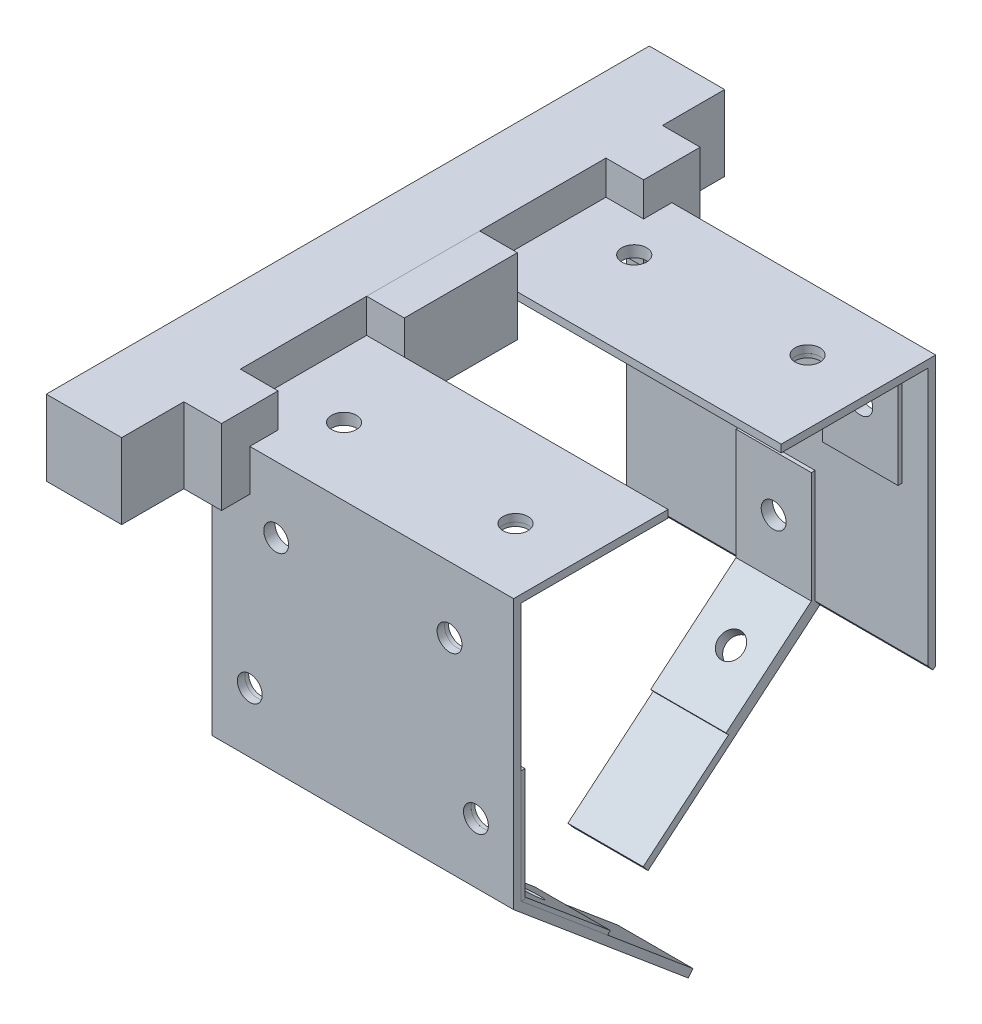
SolidWorks part; units mm, degrees
ref_plane "Front Plane" through (0, 0, 0) normal (0, 0, 1) x (1, 0, 0)
ref_plane "Top Plane" through (0, 0, 0) normal (0, 1, 0) x (1, 0, 0)
ref_plane "Right Plane" through (0, 0, 0) normal (1, 0, 0) x (0, 0, -1)
sketch "Sketch2" plane through (0, 0, 0) normal (1, 0, 0) x (0, 0, -1)
  line L0 (-19.05, 0) -> (19.05, 0) construction
  line L1 (-19.05, 0) -> (-69.85, 0)
  line L2 (-69.85, 0) -> (-69.85, -88.9)
  line L3 (-69.85, -88.9) -> (-11.4774, -137.8804)
  line L4 (19.05, 0) -> (69.85, 0)
  line L5 (69.85, 0) -> (69.85, -88.9)
  line L6 (69.85, -88.9) -> (11.4774, -137.8804)
  point P8 (0, 0)
  dimension "D1" = 38.1
  dimension "D2" = 50.8
  dimension "D3" = 88.9
  dimension "D4" = 76.2
  dimension "D5" = 130
  dimension "D6" = 130
extrude "Extrude-Thin1" add sketch "Sketch2" along normal blind 101.6 thin thin type mid plane wall 2.54
sketch "Sketch6" plane through (0, -85.5902, -71.8187) normal (0, 0.766, 0.6428) x (1, 0, 0)
  line L0 (101.6, -4.2278) -> (0, -4.2278) construction
  line L1 (38.1, -4.2278) -> (63.5, -4.2278)
  line L2 (38.1, -4.2278) -> (38.1, -79.8356)
  line L3 (38.1, -79.8356) -> (63.5, -79.8356)
  line L4 (63.5, -4.2278) -> (63.5, -79.8356)
  line L5 (101.6, -79.8356) -> (0, -79.8356) construction
  line L8 (63.5, -4.2278) -> (101.6, -4.2278) construction
  line L9 (38.1, -4.2278) -> (0, -4.2278) construction
  line L11 (38.1, -4.2278) -> (0, -4.2278)
  line L12 (38.1, -4.2278) -> (38.1, -79.8356)
  line L13 (38.1, -79.8356) -> (0, -79.8356)
  line L14 (0, -4.2278) -> (0, -79.8356)
  line L15 (101.6, -79.8356) -> (63.5, -79.8356)
  line L16 (101.6, -79.8356) -> (101.6, -4.2278)
  line L17 (101.6, -4.2278) -> (63.5, -4.2278)
  line L18 (63.5, -79.8356) -> (63.5, -4.2278)
  line M5 (0, -4.2278) -> (0, -79.8356)
  line M6 (0, -79.8356) -> (101.6, -79.8356)
  line M7 (101.6, -79.8356) -> (101.6, -4.2278)
  line M8 (101.6, -4.2278) -> (0, -4.2278)
  dimension "D1" = 25.4
extrude "Cut-Extrude2" cut sketch "Sketch6" against normal blind 11.684 contours L4 M8 M6 M7 | L2 M8 M5 M6
sketch "Sketch7" plane through (0, -85.5902, 71.8187) normal (0, 0.766, -0.6428) x (1, 0, 0)
  line L0 (101.6, 79.8356) -> (0, 79.8356) construction
  line L1 (101.6, 4.2278) -> (76.2, 4.2278)
  line L2 (101.6, 4.2278) -> (101.6, 79.8356)
  line L3 (101.6, 79.8356) -> (76.2, 79.8356)
  line L4 (76.2, 4.2278) -> (76.2, 79.8356)
  line L6 (0, 4.2278) -> (25.4, 4.2278)
  line L7 (0, 4.2278) -> (0, 79.8356)
  line L8 (0, 79.8356) -> (25.4, 79.8356)
  line L9 (25.4, 4.2278) -> (25.4, 79.8356)
  line L10 (76.2, 4.2278) -> (25.4, 4.2278)
  line L11 (76.2, 4.2278) -> (76.2, 79.8356)
  line L12 (76.2, 79.8356) -> (25.4, 79.8356)
  line L13 (25.4, 4.2278) -> (25.4, 79.8356)
  line M4 (0, 4.2278) -> (101.6, 4.2278)
  line M6 (101.6, 79.8356) -> (0, 79.8356)
  dimension "D1" = 25.4
  dimension "D2" = 25.4
extrude "Cut-Extrude3" cut sketch "Sketch7" against normal blind 11.684 contours L9 L4 M4 M6
sketch "Sketch8" plane through (0, 0, 68.58) normal (0, 0, -1) x (-1, 0, 0)
  line L0 (-76.2, -88.3078) -> (-76.2, -50.2078)
  line L1 (-76.2, -50.2078) -> (-101.6, -50.2078)
  line L2 (-101.6, -1.27) -> (-101.6, -88.3078) construction
  line L3 (-101.6, -50.2078) -> (-101.6, -88.3078)
  line L4 (-101.6, -88.3078) -> (-76.2, -88.3078)
  line L5 (0, -88.3078) -> (0, -50.2078)
  line L6 (0, -1.27) -> (0, -88.3078) construction
  line L7 (0, -50.2078) -> (-25.4, -50.2078)
  line L8 (-25.4, -50.2078) -> (-25.4, -88.3078)
  line L9 (-25.4, -88.3078) -> (0, -88.3078)
  line L10 (-101.6, -1.27) -> (0, -1.27) construction
  line L11 (-92.71, -1.27) -> (-67.31, -1.27)
  line L12 (-92.71, -1.27) -> (-92.71, -39.37)
  line L13 (-92.71, -39.37) -> (-67.31, -39.37)
  line L14 (-67.31, -1.27) -> (-67.31, -39.37)
  line L16 (-8.89, -1.27) -> (-34.29, -1.27)
  line L17 (-8.89, -1.27) -> (-8.89, -39.37)
  line L18 (-8.89, -39.37) -> (-34.29, -39.37)
  line L19 (-34.29, -1.27) -> (-34.29, -39.37)
  dimension "D1" = 38.1
  dimension "D2" = 8.89
  dimension "D3" = 8.89
extrude "Boss-Extrude1" add sketch "Sketch8" along normal blind 1.27 separate body
sketch "Sketch10" plane through (0, -85.5902, 71.8187) normal (0, 0.766, -0.6428) x (1, 0, 0)
  line L0 (76.2, 4.2278) -> (76.2, 79.8356) construction
  line L1 (101.6, 4.2278) -> (76.2, 4.2278)
  line L2 (101.6, 4.2278) -> (101.6, 42.3278)
  line L3 (101.6, 42.3278) -> (76.2, 42.3278)
  line L4 (76.2, 4.2278) -> (76.2, 42.3278)
  line L10 (0, 4.2278) -> (0, 79.8356) construction
  line L11 (25.4, 4.2278) -> (0, 4.2278)
  line L12 (25.4, 4.2278) -> (25.4, 42.3278)
  line L13 (25.4, 42.3278) -> (0, 42.3278)
  line L14 (0, 4.2278) -> (0, 42.3278)
  dimension "D1" = 38.1
  dimension "D2" = 38.1
extrude "Boss-Extrude2" add sketch "Sketch10" along normal blind 1.27 separate body
sketch "Sketch12" plane through (0, -85.5902, -71.8187) normal (0, 0.766, 0.6428) x (1, 0, 0)
  line L0 (63.5, -4.2278) -> (63.5, -79.8356) construction
  line L1 (38.1, -4.2278) -> (63.5, -4.2278)
  line L2 (38.1, -4.2278) -> (38.1, -42.3278)
  line L3 (38.1, -42.3278) -> (63.5, -42.3278)
  line L4 (63.5, -4.2278) -> (63.5, -42.3278)
  dimension "D1" = 38.1
extrude "Boss-Extrude3" add sketch "Sketch12" along normal blind 1.27 separate body
sketch "Sketch13" plane through (0, 0, -68.58) normal (0, 0, 1) x (1, 0, 0)
  line L0 (38.1, -88.3078) -> (0, -88.3078) construction
  line L1 (38.1, -88.3078) -> (63.5, -88.3078)
  line L2 (38.1, -88.3078) -> (38.1, -50.2078)
  line L3 (38.1, -50.2078) -> (63.5, -50.2078)
  line L4 (63.5, -88.3078) -> (63.5, -50.2078)
  line L5 (38.1, -88.3078) -> (0, -88.3078) construction
  line L6 (63.5, -88.3078) -> (101.6, -88.3078) construction
  line L7 (101.6, -1.27) -> (0, -1.27) construction
  line L8 (92.71, -1.27) -> (67.31, -1.27)
  line L9 (92.71, -1.27) -> (92.71, -39.37)
  line L10 (92.71, -39.37) -> (67.31, -39.37)
  line L11 (67.31, -1.27) -> (67.31, -39.37)
  line L12 (0, -1.27) -> (0, -88.3078) construction
  line L13 (34.29, -1.27) -> (8.89, -1.27)
  line L14 (34.29, -1.27) -> (34.29, -39.37)
  line L15 (34.29, -39.37) -> (8.89, -39.37)
  line L16 (8.89, -1.27) -> (8.89, -39.37)
  line L17 (101.6, -1.27) -> (101.6, -88.3078) construction
  dimension "D1" = 25.4
  dimension "D2" = 38.1
  dimension "D3" = 25.4
  dimension "D4" = 38.1
  dimension "D5" = 8.89
  dimension "D6" = 8.89
extrude "Boss-Extrude4" add sketch "Sketch13" along normal blind 1.27
sketch "Sketch14" plane through (0, -1.27, 0) normal (0, -1, 0) x (1, 0, 0)
  line L0 (101.6, 68.58) -> (0, 68.58) construction
  line L1 (8.89, 67.31) -> (34.29, 67.31)
  line L2 (8.89, 67.31) -> (8.89, 29.21)
  line L3 (8.89, 29.21) -> (34.29, 29.21)
  line L4 (34.29, 67.31) -> (34.29, 29.21)
  line L5 (67.31, 68.58) -> (92.71, 68.58)
  line L6 (67.31, 68.58) -> (67.31, 30.48)
  line L7 (67.31, 30.48) -> (92.71, 30.48)
  line L8 (92.71, 68.58) -> (92.71, 30.48)
  line L9 (67.31, -68.58) -> (34.29, -68.58) construction
  line L14 (67.31, -68.58) -> (92.71, -68.58)
  line L15 (67.31, -68.58) -> (67.31, -30.48)
  line L16 (67.31, -30.48) -> (92.71, -30.48)
  line L17 (92.71, -68.58) -> (92.71, -30.48)
  line L23 (34.29, -68.58) -> (8.89, -68.58)
  line L24 (34.29, -68.58) -> (34.29, -30.48)
  line L25 (34.29, -30.48) -> (8.89, -30.48)
  line L26 (8.89, -68.58) -> (8.89, -30.48)
  line L27 (101.6, 19.05) -> (101.6, 68.58) construction
  line L28 (101.6, -19.05) -> (101.6, -68.58) construction
  line L29 (0, -19.05) -> (0, -68.58) construction
  dimension "D1" = 25.4
  dimension "D2" = 38.1
  dimension "D3" = 8.89
  dimension "D4" = 8.89
  dimension "D5" = 8.89
extrude "Boss-Extrude5" add sketch "Sketch14" along normal blind 1.27 separate body
sketch "Sketch18" plane through (0, 0, 67.31) normal (0, 0, -1) x (-1, 0, 0)
  line L0 (-101.6, -50.2078) -> (-76.2, -88.3078) construction
  line L1 (-76.2, -50.2078) -> (-101.6, -88.3078) construction
  line L2 (-25.4, -50.2078) -> (0, -88.3078) construction
  line L3 (0, -50.2078) -> (-25.4, -88.3078) construction
  line L4 (-34.29, -39.37) -> (-8.89, -2.54) construction
  line L5 (-8.89, -39.37) -> (-34.29, -2.54) construction
  line L6 (-92.71, -39.37) -> (-67.31, -2.54) construction
  line L7 (-67.31, -39.37) -> (-67.31, -1.27) construction
  line L8 (-92.71, -2.54) -> (-67.31, -39.37) construction
  line L9 (-92.71, -1.27) -> (-92.71, -39.37) construction
  circle A0 centre (-80.01, -20.955) radius 4.191
  circle A1 centre (-21.59, -20.955) radius 4.191
  circle A2 centre (-12.7, -69.2578) radius 4.191
  circle A3 centre (-88.9, -69.2578) radius 4.191
  dimension "D1" = 8.382
  dimension "D2" = 8.382
  dimension "D3" = 8.382
  dimension "D4" = 8.382
extrude "Cut-Extrude4" cut sketch "Sketch18" against normal blind 34.798
sketch "Sketch20" plane through (0, 0, 71.12) normal (0, 0, 1) x (1, 0, 0)
  circle A0 centre (21.59, -20.955) radius 4.191
  circle A1 centre (80.01, -20.955) radius 4.191
  dimension "D1" = 8.382
  dimension "D2" = 8.382
extrude "Cut-Extrude5" cut sketch "Sketch20" against normal blind 201.168
sketch "Sketch23" plane through (0, -2.54, 0) normal (0, -1, 0) x (1, 0, 0)
  line L0 (8.89, 29.21) -> (34.29, 67.31) construction
  line L1 (34.29, 29.21) -> (8.89, 67.31) construction
  line L2 (92.71, 30.48) -> (67.31, 67.31) construction
  line L3 (67.31, 68.58) -> (67.31, 30.48) construction
  line L4 (67.31, 30.48) -> (92.71, 67.31) construction
  line L5 (92.71, 30.48) -> (92.71, 68.58) construction
  line L6 (34.29, -30.48) -> (8.89, -68.58) construction
  line L7 (8.89, -30.48) -> (8.89, -68.58) construction
  line L8 (8.89, -30.48) -> (34.29, -68.58) construction
  line L9 (92.71, -30.48) -> (67.31, -68.58) construction
  line L10 (67.31, -30.48) -> (92.71, -68.58) construction
  circle A0 centre (80.01, -49.53) radius 4.191
  circle A1 centre (21.59, -49.53) radius 4.191
  circle A2 centre (80.01, 48.895) radius 4.191
  circle A3 centre (21.59, 48.26) radius 4.191
  dimension "D1" = 8.382
  dimension "D2" = 8.382
  dimension "D3" = 8.382
  dimension "D4" = 8.382
extrude "Cut-Extrude6" cut sketch "Sketch23" against normal blind 201.168
sketch "Sketch24" plane through (0, 0, -67.31) normal (0, 0, 1) x (1, 0, 0)
  line L1 (38.1, -50.2078) -> (63.5, -50.2078) construction
  line L2 (38.1, -50.2078) -> (38.1, -87.7156) construction
  line L3 (38.1, -87.7156) -> (63.5, -87.7156) construction
  line L4 (63.5, -50.2078) -> (63.5, -87.7156) construction
  line L5 (38.1, -50.2078) -> (63.5, -87.7156) construction
  line L6 (38.1, -87.7156) -> (63.5, -50.2078) construction
  circle A0 centre (50.8, -68.9617) radius 4.191
  point P4 (50.8, -68.9617)
  dimension "D1" = 8.382
extrude "Cut-Extrude7" cut sketch "Sketch24" against normal blind 201.168
sketch "Sketch25" plane through (0, -84.6173, 71.0024) normal (0, 0.766, -0.6428) x (1, 0, 0)
  line L0 (76.2, 4.2278) -> (101.6, 4.2278) construction
  line L1 (76.2, 42.3278) -> (101.6, 42.3278) construction
  line L2 (76.2, 42.3278) -> (76.2, 4.2278) construction
  line L3 (76.2, 4.2278) -> (101.6, 4.2278) construction
  line L4 (101.6, 42.3278) -> (101.6, 4.2278) construction
  line L5 (76.2, 42.3278) -> (101.6, 4.2278) construction
  line L6 (76.2, 4.2278) -> (101.6, 42.3278) construction
  line L7 (101.6, 4.2278) -> (101.6, 42.3278) construction
  line L8 (25.4, 4.2278) -> (25.4, 42.3278) construction
  line L10 (0, 42.3278) -> (25.4, 42.3278) construction
  line L11 (0, 42.3278) -> (0, 4.2278) construction
  line L12 (0, 4.2278) -> (25.4, 4.2278) construction
  line L13 (25.4, 42.3278) -> (25.4, 4.2278) construction
  line L14 (0, 42.3278) -> (25.4, 4.2278) construction
  line L15 (0, 4.2278) -> (25.4, 42.3278) construction
  circle A0 centre (12.7, 23.2778) radius 4.191
  circle A1 centre (88.9, 23.2778) radius 4.191
  point P4 (88.9, 23.2778)
  point P16 (12.7, 23.2778)
  dimension "D1" = 8.382
  dimension "D2" = 8.382
extrude "Cut-Extrude8" cut sketch "Sketch25" against normal blind 201.168 contours A0 | A1
sketch "Sketch26" plane through (0, -84.6173, -71.0024) normal (0, 0.766, 0.6428) x (1, 0, 0)
  line L1 (38.1, -4.82) -> (63.5, -4.82) construction
  line L2 (38.1, -4.82) -> (38.1, -42.3278) construction
  line L3 (38.1, -42.3278) -> (63.5, -42.3278) construction
  line L4 (63.5, -4.82) -> (63.5, -42.3278) construction
  line L5 (38.1, -4.82) -> (63.5, -42.3278) construction
  line L6 (38.1, -42.3278) -> (63.5, -4.82) construction
  circle A0 centre (50.8, -23.5739) radius 4.191
  point P4 (50.8, -23.5739)
  dimension "D1" = 8.382
extrude "Cut-Extrude9" cut sketch "Sketch26" against normal blind 201.168
sketch "Sketch27" plane through (0, 0, 0) normal (1, 0, 0) x (0, 0, -1)
  line L1 (101.6, 12.7) -> (-101.6, 12.7)
  line L2 (101.6, 12.7) -> (101.6, -12.7)
  line L3 (101.6, -12.7) -> (-101.6, -12.7)
  line L4 (-101.6, 12.7) -> (-101.6, -12.7)
  line L5 (101.6, 12.7) -> (-101.6, -12.7) construction
  line L6 (101.6, -12.7) -> (-101.6, 12.7) construction
  point P0 (0, 0)
  dimension "D1" = 203.2
  dimension "D2" = 25.4
extrude "Boss-Extrude6" add sketch "Sketch27" against normal blind 25.4
sketch "Sketch28" plane through (0, 0, 0) normal (1, 0, 0) x (0, 0, -1)
  line L0 (-68.58, -12.7) -> (68.58, -12.7) construction
  line L1 (0, -12.7) -> (-19.05, -12.7)
  line L2 (0, -12.7) -> (0, 12.7)
  line L3 (0, 12.7) -> (-19.05, 12.7)
  line L4 (-19.05, -12.7) -> (-19.05, 12.7)
  line L5 (0, -12.7) -> (-19.05, 12.7) construction
  line L6 (0, 12.7) -> (-19.05, -12.7) construction
  line L7 (101.6, 12.7) -> (-101.6, 12.7) construction
  line L9 (0, -12.7) -> (19.05, -12.7)
  line L10 (0, -12.7) -> (0, 12.7)
  line L11 (0, 12.7) -> (19.05, 12.7)
  line L12 (19.05, -12.7) -> (19.05, 12.7)
  line L13 (0, -12.7) -> (19.05, 12.7) construction
  line L14 (0, 12.7) -> (19.05, -12.7) construction
  line L15 (19.05, -1.27) -> (19.05, 1.27) construction
  line L16 (-19.05, 1.27) -> (-19.05, -1.27) construction
  point P4 (-9.525, 0)
  point P11 (9.525, 0)
  line M8 (19.05, -1.27) -> (19.05, 1.27)
  line M13 (101.6, 12.7) -> (-101.6, 12.7)
  line M21 (-68.58, -12.7) -> (68.58, -12.7)
extrude "Boss-Extrude7" add sketch "Sketch28" along normal blind 12.7 separate body contours L12 L2 M21 M8 M13
sketch "Sketch29" plane through (0, 0, 0) normal (1, 0, 0) x (0, 0, -1)
  line L0 (-80.645, 12.7) -> (-80.645, -12.7)
  line L1 (101.6, 12.7) -> (-101.6, 12.7) construction
  line L2 (-101.6, -12.7) -> (-71.12, -12.7) construction
  line L3 (-80.645, -12.7) -> (-61.595, -12.7)
  line L4 (-61.595, -12.7) -> (-61.595, 12.7)
  line L5 (-61.595, 12.7) -> (-80.645, 12.7)
  line L6 (80.645, -12.7) -> (80.645, 12.7)
  line L7 (71.12, -12.7) -> (101.6, -12.7) construction
  line L8 (80.645, 12.7) -> (61.595, 12.7)
  line L9 (61.595, 12.7) -> (61.595, -12.7)
  line L10 (61.595, -12.7) -> (80.645, -12.7)
  line L11 (-80.645, 12.7) -> (-61.595, -12.7) construction
  line L12 (-61.595, 12.7) -> (-80.645, -12.7) construction
  line L13 (61.595, 12.7) -> (80.645, -12.7) construction
  line L14 (80.645, 12.7) -> (61.595, -12.7) construction
  point P12 (71.12, -12.7)
  point P16 (-71.12, -12.7)
  dimension "D1" = 19.05
  dimension "D2" = 19.05
extrude "Boss-Extrude8" add sketch "Sketch29" along normal blind 12.7
